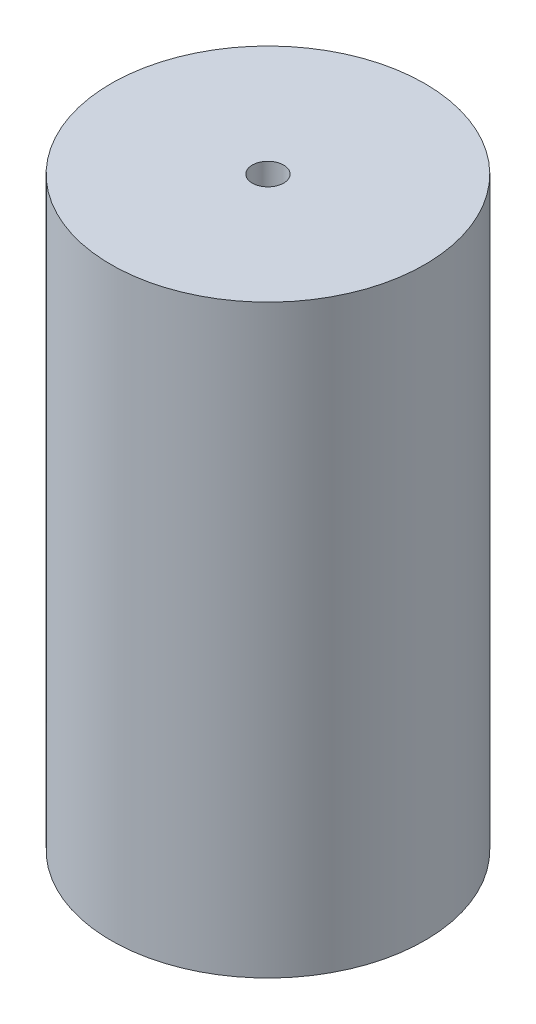
SolidWorks part; units mm, degrees
ref_plane "Front Plane" through (0, 0, 0) normal (0, 0, 1) x (1, 0, 0)
ref_plane "Top Plane" through (0, 0, 0) normal (0, 1, 0) x (1, 0, 0)
ref_plane "Right Plane" through (0, 0, 0) normal (1, 0, 0) x (0, 0, -1)
sketch "Sketch1" plane through (0, 0, 0) normal (0, 1, 0) x (1, 0, 0)
  circle A0 centre (0, 0) radius 19.177
  circle A1 centre (0, 0) radius 25.527
  dimension "D1" = 38.354
  dimension "D2" = 6.35
extrude "Boss-Extrude1" add sketch "Sketch1" along normal blind 76.2
sketch "Sketch2" plane through (0, 76.2, 0) normal (0, 1, 0) x (1, 0, 0)
  circle A0 centre (0, 0) radius 25.527 construction
  circle A1 centre (0, 0) radius 25.527
extrude "Boss-Extrude2" add sketch "Sketch2" along normal blind 19.05
sketch "Sketch3" plane through (0, 95.25, 0) normal (0, 1, 0) x (1, 0, 0)
  point P0 (0, 0)
hole_wizard "Tap Drill for 1/4-20 Tap1" positions "3DSketch1" profile "Sketch5" hole size "1/4-20" standard "ANSI Inch" end condition up to next
sketch3d "3DSketch1"
  point P0 (0, 95.25, 0)
sketch "Sketch5" plane through (0, 95.25, 0) normal (1, 0, 0) x (0, 0, 1)
  line L0 (0, 0) -> (0, 19.05)
  line L1 (0, 19.05) -> (2.5527, 19.05)
  line L2 (2.5527, 19.05) -> (2.5527, 0)
  line L5 (2.5527, 0) -> (0, 0)
  line L11 (0, -6.35) -> (0, 107.95) construction
  dimension "Thru Hole Dia." = 5.1054
  dimension "Thru Hole Depth" = 19.05
fillet "Fillet1" radius 2.54 1 edges at (0, 0, 19.177)
